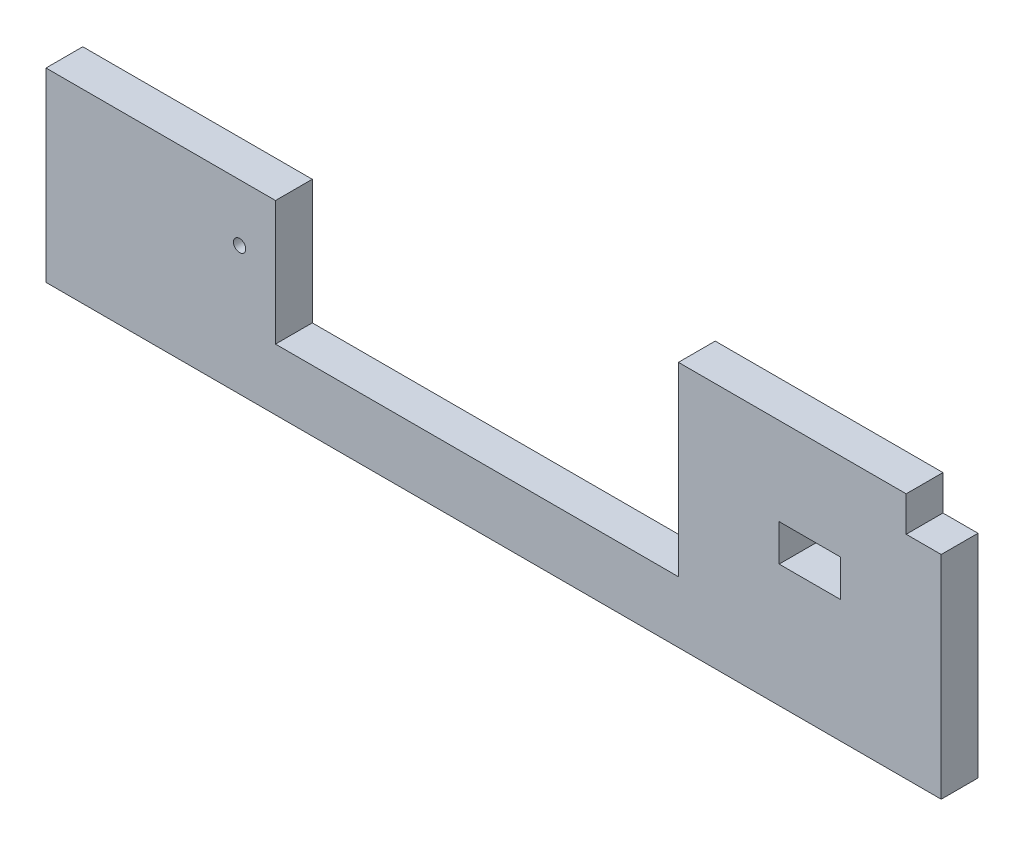
SolidWorks part; units mm, degrees
ref_plane "Front Plane" through (0, 0, 0) normal (0, 0, 1) x (1, 0, 0)
ref_plane "Top Plane" through (0, 0, 0) normal (0, 1, 0) x (1, 0, 0)
ref_plane "Right Plane" through (0, 0, 0) normal (1, 0, 0) x (0, 0, -1)
sketch "Sketch1" plane through (0, 0, 0) normal (0, 0, 1) x (1, 0, 0)
  line L1 (-85.0624, -35.0708) -> (44.7316, -35.0708)
  line L2 (-85.0624, -35.0708) -> (-85.0624, -59.4548)
  line L3 (-85.0624, -59.4548) -> (44.7316, -59.4548)
  line L4 (44.7316, -35.0708) -> (44.7316, -59.4548)
  dimension "D1" = 129.794
  dimension "D2" = 24.384
extrude "Boss-Extrude1" add sketch "Sketch1" along normal blind 5.334
sketch "Sketch3" plane through (0, 0, 5.334) normal (0, 0, 1) x (1, 0, 0)
  line L0 (44.7316, -35.0708) -> (-85.0624, -35.0708) construction
  line L1 (-51.7884, -35.0708) -> (6.6316, -35.0708)
  line L2 (-51.7884, -35.0708) -> (-51.7884, -53.1048)
  line L3 (-51.7884, -53.1048) -> (6.6316, -53.1048)
  line L4 (6.6316, -35.0708) -> (6.6316, -53.1048)
  line L5 (44.7316, -59.4548) -> (44.7316, -35.0708) construction
  dimension "D1" = 38.1
  dimension "D2" = 58.42
  dimension "D3" = 18.034
extrude "Cut-Extrude1" cut sketch "Sketch3" against normal through all
sketch "Sketch4" plane through (0, 0, 5.334) normal (0, 0, 1) x (1, 0, 0)
  line L0 (-51.7884, -35.0708) -> (-85.0624, -35.0708) construction
  line L3 (-68.4254, -40.0238) -> (-68.4254, -47.5431) construction
  circle A0 centre (-56.9954, -43.3258) radius 0.889
  dimension "D1" = 1.778
  dimension "D2" = 8.255
  dimension "D3" = 11.43
sketch "Sketch6" plane through (0, -35.0708, 0) normal (0, 1, 0) x (1, 0, 0)
  line L1 (6.6316, 0) -> (44.7316, 0)
  line L2 (6.6316, 0) -> (6.6316, -5.334)
  line L3 (6.6316, -5.334) -> (44.7316, -5.334)
  line L4 (44.7316, 0) -> (44.7316, -5.334)
extrude "Boss-Extrude2" add sketch "Sketch6" along normal blind 8.89
sketch "Sketch7" plane through (0, 0, 5.334) normal (0, 0, 1) x (1, 0, 0)
  line L1 (44.7316, -26.1808) -> (39.6516, -26.1808)
  line L2 (44.7316, -26.1808) -> (44.7316, -31.2608)
  line L3 (44.7316, -31.2608) -> (39.6516, -31.2608)
  line L4 (39.6516, -26.1808) -> (39.6516, -31.2608)
  dimension "D1" = 5.08
  dimension "D2" = 5.08
extrude "Cut-Extrude4" cut sketch "Sketch7" against normal through all
sketch "Sketch8" plane through (0, 0, 5.334) normal (0, 0, 1) x (1, 0, 0)
  line L0 (6.6316, -26.1808) -> (39.6516, -26.1808) construction
  line L1 (21.2366, -38.8808) -> (30.1266, -38.8808)
  line L2 (21.2366, -38.8808) -> (21.2366, -44.2148)
  line L3 (21.2366, -44.2148) -> (30.1266, -44.2148)
  line L4 (30.1266, -38.8808) -> (30.1266, -44.2148)
  line L5 (44.7316, -31.2608) -> (6.6316, -31.2608) construction
  line L6 (6.6316, -53.1048) -> (6.6316, -26.1808) construction
  line L7 (25.6816, -31.2608) -> (25.6816, -59.4548) construction
  line L8 (-85.0624, -59.4548) -> (44.7316, -59.4548) construction
  dimension "D1" = 18.034
  dimension "D2" = 5.334
  dimension "D3" = 8.89
  dimension "D4" = 4.445
extrude "Cut-Extrude5" cut sketch "Sketch8" against normal through all
extrude "Cut-Extrude6" cut sketch "Sketch4" against normal through all
sketch "Sketch9" plane through (0, -59.4548, 0) normal (0, -1, 0) x (-1, 0, 0)
  line L1 (85.0624, -5.334) -> (-44.7316, -5.334)
  line L2 (85.0624, -5.334) -> (85.0624, 0)
  line L3 (85.0624, 0) -> (-44.7316, 0)
  line L4 (-44.7316, -5.334) -> (-44.7316, 0)
extrude "Boss-Extrude3" add sketch "Sketch9" along normal blind 2.54
equation "\"MDF\"= .21in"
equation "\"Foamcore\"= .13in"
equation "\"Gmaterial\"= \"MDF\""
equation "\"D2@Sketch1\"=\"MDF\"+.25+.5"
equation "\"D1@Boss-Extrude1\"=\"MDF\""
equation "\"D3@Sketch3\"=\"MDF\"+.5"
equation "\"D2@Sketch8\"=\"MDF\""
